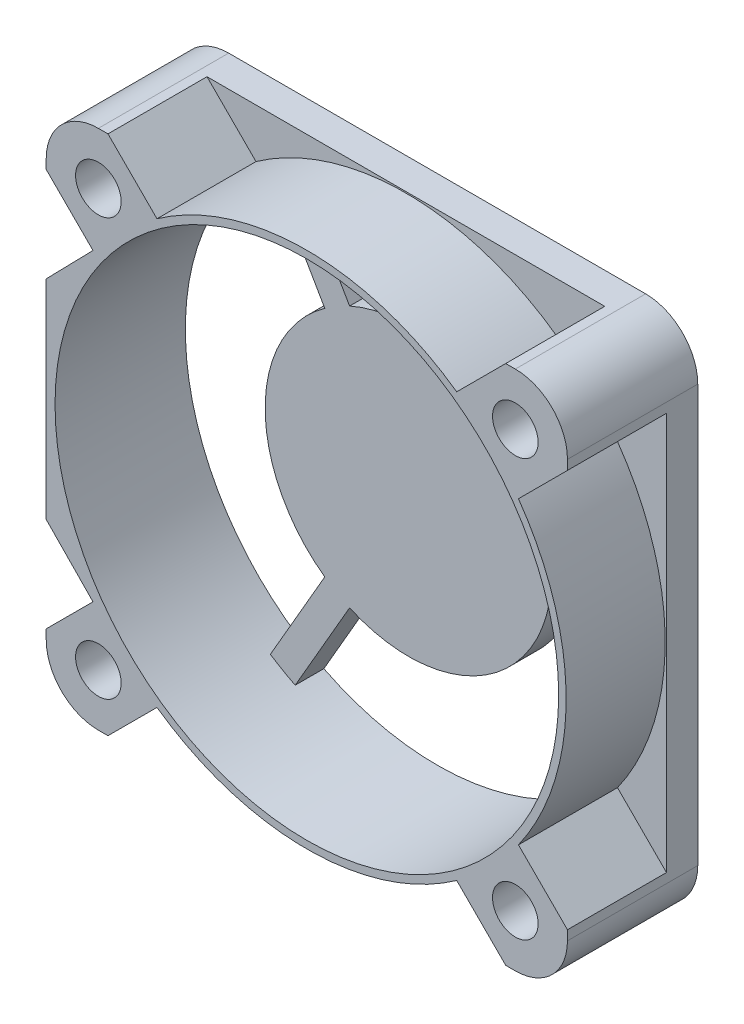
SolidWorks part; units mm, degrees
ref_plane "Front" through (0, 0, 0) normal (0, 0, 1) x (1, 0, 0)
ref_plane "Top" through (0, 0, 0) normal (0, 1, 0) x (1, 0, 0)
ref_plane "Right" through (0, 0, 0) normal (1, 0, 0) x (0, 0, -1)
sketch "Sketch21" plane through (0, 0, 0) normal (0, 0, 1) x (1, 0, 0)
  line L0 (20, 20) -> (-20, 20)
  line L1 (-20, 20) -> (-20, -20)
  line L2 (-20, -20) -> (20, -20)
  line L3 (20, -20) -> (20, 20)
  line L4 (-20, -20) -> (20, 20) construction
  line L5 (-20, 20) -> (20, -20) construction
  dimension "D1" = 40
extrude "Boss-Extrude4" add sketch "Sketch21" along normal mid plane 10 separate body
fillet "Fillet3" radius 4 4 edges at (-20, -20, 0) (20, 20, 0) (20, -20, 0) (-20, 20, 0)
sketch "Sketch22" plane through (0, 0, 5) normal (0, 0, 1) x (1, 0, 0)
  circle A0 centre (0, 0) radius 19.325
  dimension "D1" = 38.65
extrude "Cut-Extrude11" cut sketch "Sketch22" against normal through all
sketch "Sketch23" plane through (0, 0, 5) normal (0, 0, 1) x (1, 0, 0)
  line L0 (16, 20) -> (-16, 20) construction
  line L1 (0, 0) -> (-11.3307, 11.3307) construction
  line L2 (15.2624, 20) -> (11.5018, 16.2394)
  line L6 (-15.2624, 20) -> (-11.5018, 16.2394)
  line L7 (15.2624, 20) -> (-15.2624, 20)
  line L16 (0, 22.353) -> (0, 0) construction
  line L17 (0, 0) -> (13.1623, 0) construction
  circle A0 centre (0, 0) radius 19.325 construction
  arc A3 (-11.5018, 16.2394) -> (11.5018, 16.2394) centre (0, 0) cw
  dimension "D1" = 19.9
  dimension "D2" = 45
  dimension "D3" = 6.7
extrude "Cut-Extrude12" cut sketch "Sketch23" against normal blind 7.6
sketch "Sketch30" plane through (0, 0, 5) normal (0, 0, 1) x (1, 0, 0)
  circle A0 centre (-16, 16) radius 1.75
  arc A1 (-16, 20) -> (-20, 16) centre (-16, 16) ccw construction
  dimension "D1" = 3.5
extrude "Cut-Extrude13" cut sketch "Sketch30" against normal up to next
pattern_circular "CirPattern2" count 4 over 360 about axis through (0, 0, 0) along (0, 0, 1) of "Cut-Extrude13", "Cut-Extrude12"
sketch "Sketch20" plane through (0, 0, -5) normal (0, 0, -1) x (-1, 0, 0)
  line L0 (6.4251, 8.9285) -> (10.5995, 16.1588)
  line L1 (-10.9449, 1.1) -> (-19.2937, 1.1)
  line L2 (-19.2937, -1.1) -> (-10.9449, -1.1)
  line L3 (8.6942, -17.2588) -> (4.5198, -10.0285)
  line L4 (6.4251, -8.9285) -> (10.5995, -16.1588)
  line L5 (8.6942, 17.2588) -> (4.5198, 10.0285)
  line L6 (0, 0) -> (-8.108, 0) construction
  line L7 (9.6625, 16.7359) -> (0, 0) construction
  arc A0 (10.5995, 16.1588) -> (8.6942, 17.2588) centre (0, 0) ccw
  arc A1 (4.5198, 10.0285) -> (-10.9449, 1.1) centre (0, 0) ccw
  arc A2 (-19.2937, 1.1) -> (-19.2937, -1.1) centre (0, 0) ccw
  arc A3 (-10.9449, -1.1) -> (4.5198, -10.0285) centre (0, 0) ccw
  arc A4 (10.5995, -16.1588) -> (8.6942, -17.2588) centre (0, 0) cw
  arc A5 (6.4251, -8.9285) -> (6.4251, 8.9285) centre (0, 0) ccw
  circle A6 centre (0, 0) radius 19.325 construction
  dimension "D1" = 11
  dimension "D2" = 2.2
  dimension "D3" = 120
extrude "Boss-Extrude3" add sketch "Sketch20" against normal blind 2.2
sketch "Sketch31" plane through (0, 0, 5) normal (0, 0, 1) x (1, 0, 0)
  line L0 (-14.2403, 13.9005) -> (-20, 8)
  line L1 (-20, 15.2624) -> (-20, -15.2624) construction
  line L2 (-20, 8) -> (-20, -8)
  line L3 (-20, -8) -> (-14.2403, -13.9005)
  line L4 (0, 0) -> (-20, 0) construction
  arc A0 (-16.2394, 11.5018) -> (-16.2394, -11.5018) centre (0, 0) ccw construction
  arc A1 (-16.2394, 11.5018) -> (-16.2394, -11.5018) centre (0, 0) ccw construction
  arc A2 (-14.2403, 13.9005) -> (-14.2403, -13.9005) centre (0, 0) ccw
  dimension "D1" = 16
extrude "Boss-Extrude5" add sketch "Sketch31" against normal up to body
